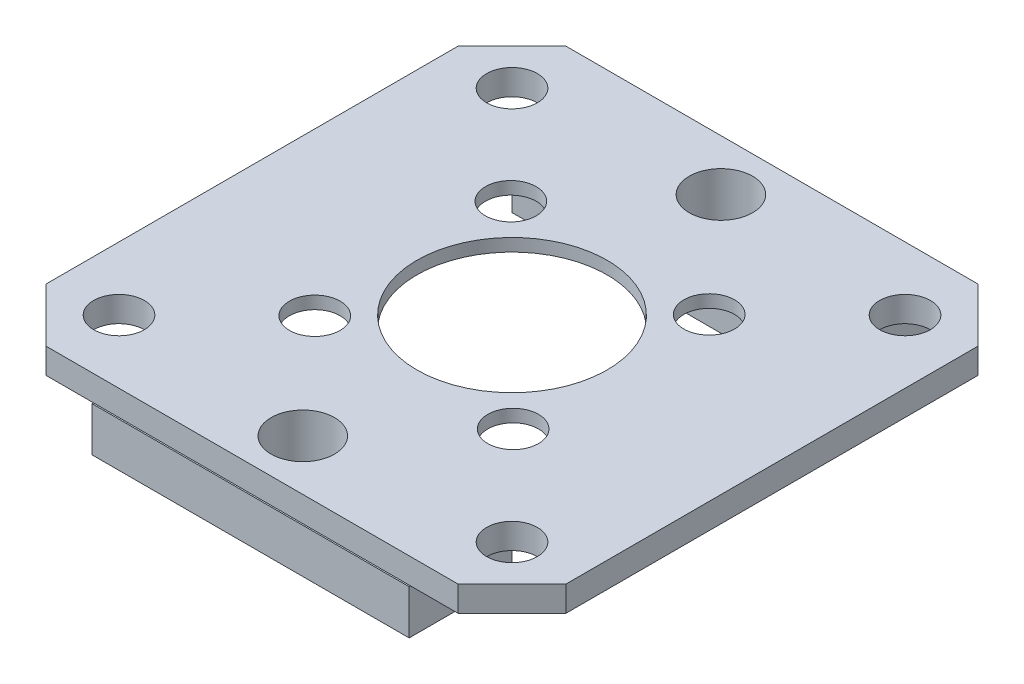
SolidWorks part; units mm, degrees
ref_plane "Front Plane" through (0, 0, 0) normal (0, 0, 1) x (1, 0, 0)
ref_plane "Top Plane" through (0, 0, 0) normal (0, 1, 0) x (1, 0, 0)
ref_plane "Right Plane" through (0, 0, 0) normal (1, 0, 0) x (0, 0, -1)
sketch "Sketch2" plane through (0, 0, 0) normal (0, 1, 0) x (1, 0, 0)
  line L1 (-20.5, -20.5) -> (20.5, -20.5)
  line L2 (-20.5, -20.5) -> (-20.5, 20.5)
  line L3 (-20.5, 20.5) -> (20.5, 20.5)
  line L4 (20.5, -20.5) -> (20.5, 20.5)
  line L5 (-20.5, -20.5) -> (20.5, 20.5) construction
  line L6 (-20.5, 20.5) -> (20.5, -20.5) construction
  point P0 (0, 0)
  dimension "D1" = 41
  dimension "D2" = 41
extrude "Boss-Extrude1" add sketch "Sketch2" along normal blind 2
sketch "Sketch3" plane through (0, 0, 0) normal (0, -1, 0) x (1, 0, 0)
  line L0 (-7.7323, -7.8238) -> (0, 0) construction
  line L5 (-7.7323, -7.8238) -> (7.7323, -7.8238) construction
  line L6 (-7.7323, -7.8238) -> (-7.7323, 7.8238) construction
  line L7 (-7.7323, 7.8238) -> (7.7323, 7.8238) construction
  line L8 (7.7323, -7.8238) -> (7.7323, 7.8238) construction
  line L9 (0, 0) -> (7.7323, 7.8238) construction
  line L10 (0, 0) -> (7.7323, -7.8238) construction
  line L11 (-7.7323, 7.8238) -> (0, 0) construction
  arc A1 (7.7323, 7.8238) -> (-7.7323, 7.8238) centre (0, 0) ccw construction
  arc A2 (-7.7323, -7.8238) -> (7.7323, -7.8238) centre (0, 0) ccw construction
  arc A3 (-7.7323, 7.8238) -> (-7.7323, -7.8238) centre (0, 0) ccw construction
  arc A4 (7.7323, -7.8238) -> (7.8544, 7.7012) centre (0, 0) ccw construction
  circle A5 centre (-7.7323, 7.8238) radius 2
  circle A10 centre (7.8238, 7.7323) radius 2
  circle A12 centre (7.7323, -7.8238) radius 2
  circle A13 centre (-7.8238, -7.7323) radius 2
  arc A14 (7.8544, 7.7012) -> (7.7323, 7.8238) centre (0, 0) ccw construction
  point P5 (0, 0)
  point P15 (-1.4144, -0.0142)
  point P19 (0, 0)
  dimension "D1" = 22
  dimension "D2" = 4
  dimension "D4" = 4
extrude "Cut-Extrude1" cut sketch "Sketch3" against normal through all
sketch "Sketch4" plane through (0, 2, 0) normal (0, 1, 0) x (1, 0, 0)
  circle A0 centre (0, 0) radius 7.5
  dimension "D1" = 15
extrude "Cut-Extrude2" cut sketch "Sketch4" against normal through all
sketch "Sketch5" plane through (0, 0, 0) normal (0, -1, 0) x (1, 0, 0)
  line L1 (-12.5, -12.5) -> (12.5, -12.5)
  line L2 (-12.5, -12.5) -> (-12.5, 12.5)
  line L3 (-12.5, 12.5) -> (12.5, 12.5)
  line L4 (12.5, -12.5) -> (12.5, 12.5)
  line L5 (-12.5, -12.5) -> (12.5, 12.5) construction
  line L6 (-12.5, 12.5) -> (12.5, -12.5) construction
  point P0 (0, 0)
  dimension "D1" = 25
  dimension "D2" = 25
extrude "Cut-Extrude3" cut sketch "Sketch5" against normal blind 1
sketch "Sketch6" plane through (0, 2, 0) normal (0, 1, 0) x (1, 0, 0)
  line L0 (-20.5, 16.2574) -> (-16.2574, 20.5)
  line L1 (-20.5, 20.5) -> (-20.5, -20.5) construction
  line L2 (20.5, 20.5) -> (-20.5, 20.5) construction
  line L4 (16.2574, 20.5) -> (20.5, 16.2574)
  line L5 (20.5, -20.5) -> (20.5, 20.5) construction
  line L7 (20.5, -16.2574) -> (16.2574, -20.5)
  line L8 (-20.5, -20.5) -> (20.5, -20.5) construction
  line L10 (-16.2574, -20.5) -> (-20.5, -16.2574)
  line L12 (-2.4898, 0) -> (5.6129, 0) construction
  line L13 (0, 5.0948) -> (0, 0) construction
  line L14 (0, 0) -> (3.8649, 3.8649) construction
  line L15 (-20.5, -16.2574) -> (-20.5, -20.5)
  line L16 (-20.5, -20.5) -> (-16.2574, -20.5)
  line L17 (16.2574, -20.5) -> (20.5, -20.5)
  line L18 (20.5, -20.5) -> (20.5, -16.2574)
  line L19 (20.5, 16.2574) -> (20.5, 20.5)
  line L20 (20.5, 20.5) -> (16.2574, 20.5)
  line L21 (-16.2574, 20.5) -> (-20.5, 20.5)
  line L22 (-20.5, 20.5) -> (-20.5, 16.2574)
  dimension "D1" = 6
  dimension "D2" = 6
  dimension "D3" = 45
  dimension "D4" = 6
  dimension "D5" = 6
extrude "Cut-Extrude4" cut sketch "Sketch6" against normal through all
sketch "Sketch7" plane through (0, 0, 0) normal (0, -1, 0) x (1, 0, 0)
  line L0 (-15.5, 15.5) -> (0, 0) construction
  line L1 (-15.5, -15.5) -> (15.5, -15.5) construction
  line L2 (-15.5, -15.5) -> (-15.5, 15.5) construction
  line L3 (-15.5, 15.5) -> (15.5, 15.5) construction
  line L4 (15.5, -15.5) -> (15.5, 15.5) construction
  line L5 (-15.5, -15.5) -> (0, 0) construction
  line L6 (0, 0) -> (15.5, -15.5) construction
  line L7 (0, 0) -> (15.5, 15.5) construction
  arc A0 (-15.5, -15.5) -> (15.5, -15.5) centre (0, 0) ccw construction
  arc A1 (-15.5, 15.5) -> (-15.5, -15.5) centre (0, 0) ccw construction
  arc A2 (15.5, -15.5) -> (15.5, 15.5) centre (0, 0) ccw construction
  arc A3 (15.5, 15.5) -> (-15.5, 15.5) centre (0, 0) ccw construction
  circle A4 centre (-15.5, 15.5) radius 2
  circle A5 centre (15.5, 15.5) radius 2
  circle A6 centre (15.5, -15.5) radius 2
  circle A7 centre (-15.5, -15.5) radius 2
  point P7 (0, 0)
  point P8 (0, 0)
  point P9 (0, 0)
  point P16 (0, 0)
  dimension "D2" = 4
  dimension "D4" = 31
  dimension "D3" = 4
extrude "Cut-Extrude5" cut sketch "Sketch7" against normal through all
sketch "Sketch8" plane through (0, 0, 0) normal (0, -1, 0) x (1, 0, 0)
  line L0 (-12.5, -12.5) -> (-12.5, 12.5) construction
  line L1 (-12.5, -12.5) -> (-20.477, -12.5) construction
  line L2 (-12.5, 12.5) -> (-20.477, 12.5) construction
  line L3 (-20.477, -12.5) -> (-20.477, 12.5) construction
  line L4 (12.5, -12.5) -> (12.5, 12.5) construction
  line L5 (12.5, -12.5) -> (20.4876, -12.5) construction
  line L6 (12.5, 12.5) -> (20.4876, 12.5) construction
  line L7 (20.4876, -12.5) -> (20.4876, 12.5) construction
  line L8 (-12.5, 12.5) -> (12.5, 12.5)
  line L9 (-12.5, 12.5) -> (-12.5, 20.611)
  line L10 (12.5, 12.5) -> (12.5, 20.611)
  line L11 (-12.5, 20.611) -> (12.5, 20.611)
  line L12 (12.5, -12.5) -> (-12.5, -12.5)
  line L13 (12.5, -12.5) -> (12.5, -20.4578)
  line L14 (-12.5, -12.5) -> (-12.5, -20.4578)
  line L15 (12.5, -20.4578) -> (-12.5, -20.4578)
extrude "Boss-Extrude2" add sketch "Sketch8" along normal blind 3.5
sketch "Sketch9" plane through (0, -3.5, 0) normal (0, -1, 0) x (1, 0, 0)
  circle A0 centre (0, 16.5) radius 2.5
  circle A1 centre (0, -16.4789) radius 2.5
  dimension "D1" = 5
extrude "Cut-Extrude6" cut sketch "Sketch9" against normal through all
